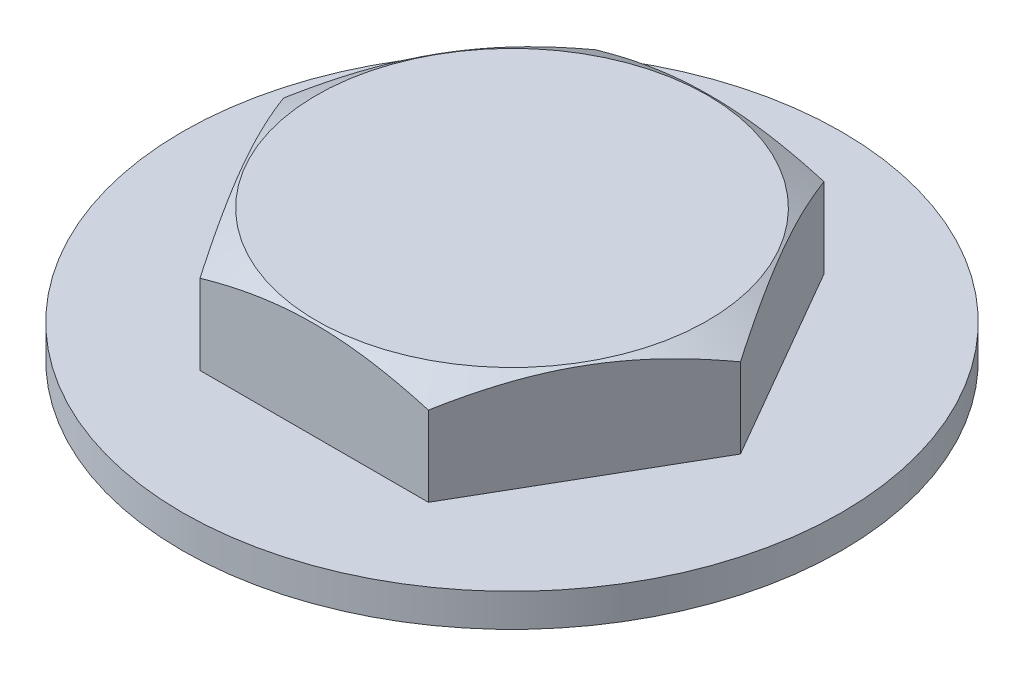
SolidWorks part; units mm, degrees
ref_plane "前视基准面" through (0, 0, 0) normal (0, 0, 1) x (1, 0, 0)
ref_plane "上视基准面" through (0, 0, 0) normal (0, 1, 0) x (1, 0, 0)
ref_plane "右视基准面" through (0, 0, 0) normal (1, 0, 0) x (0, 0, -1)
sketch "草图2" plane through (0, 0, 0) normal (0, 1, 0) x (1, 0, 0)
  circle A0 centre (0, 0) radius 2.5
  dimension "D1" = 5
extrude "凸台-拉伸1" add sketch "草图2" along normal blind 5
sketch "草图3" plane through (0, 5, 0) normal (0, 1, 0) x (1, 0, 0)
  circle A0 centre (0, 0) radius 10
  dimension "D1" = 20
extrude "凸台-拉伸2" add sketch "草图3" along normal blind 1
sketch "草图4" plane through (0, 6, 0) normal (0, 1, 0) x (1, 0, 0)
  line L0 (0, 0) -> (9.8855, 0) construction
  line L1 (3.4641, 6) -> (-3.4641, 6)
  line L2 (-3.4641, 6) -> (-6.9282, 0)
  line L3 (-6.9282, 0) -> (-3.4641, -6)
  line L4 (-3.4641, -6) -> (3.4641, -6)
  line L5 (3.4641, -6) -> (6.9282, 0)
  line L6 (6.9282, 0) -> (3.4641, 6)
  circle A0 centre (0, 0) radius 6 construction
  dimension "D1" = 12
extrude "凸台-拉伸3" add sketch "草图4" along normal blind 3
sketch "草图8" plane through (0, 0, 0) normal (0, 0, 1) x (1, 0, 0)
  line L0 (-6.9282, 9) -> (-5.9282, 9)
  line L1 (-6.9282, 9) -> (-3.4641, 9) construction
  line L2 (-5.9282, 9) -> (-6.9282, 8.4226)
  line L5 (-6.9282, 8.4226) -> (-6.9282, 9)
  line L6 (-6.9282, 9) -> (-6.9282, 6) construction
  line L7 (0, 0) -> (0, 10.0747) construction
  dimension "D1" = 1
  dimension "D2" = 30
revolve "切除-旋转1" cut sketch "草图8" angle 360 about L7
chamfer "倒角1" distance 0.5 angle 45 1 edges at (0, 0, 2.5)
